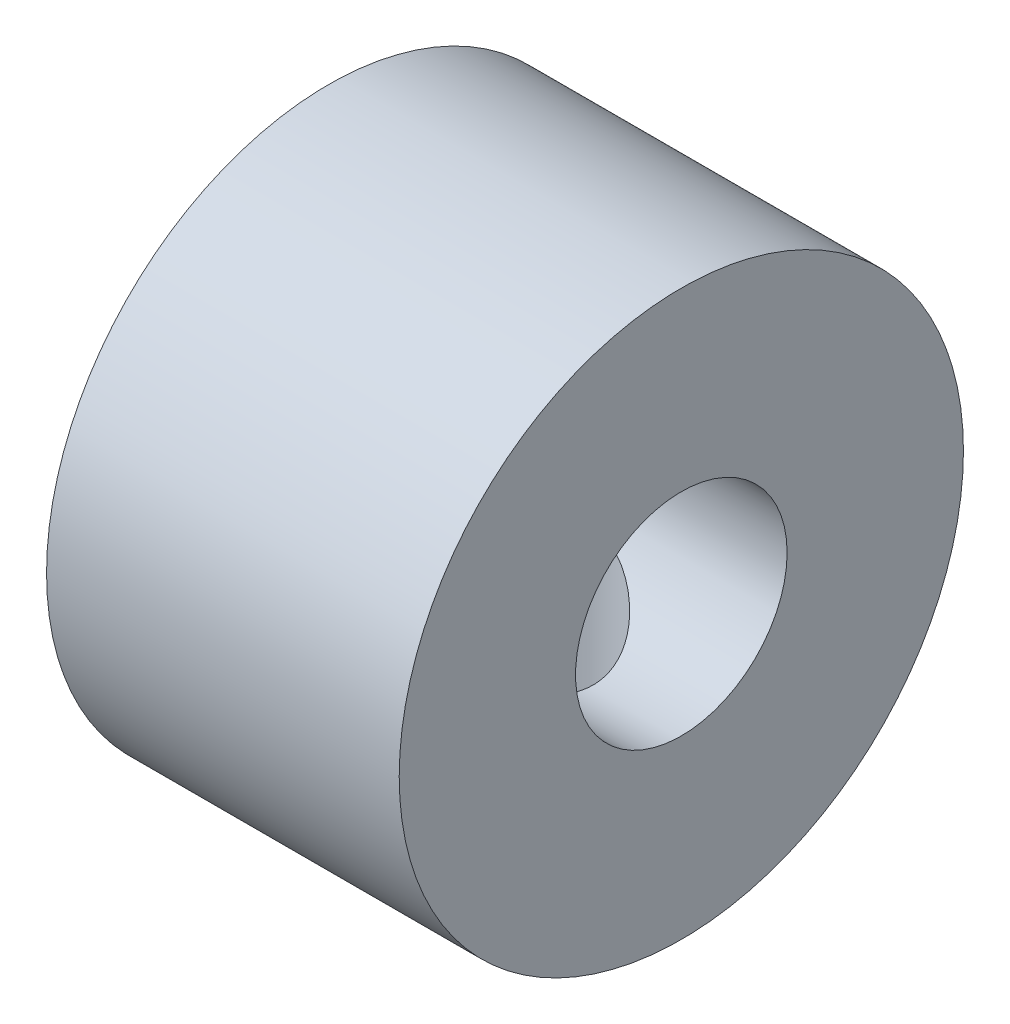
SolidWorks part; units mm, degrees
ref_plane "Front Plane" through (0, 0, 0) normal (0, 0, 1) x (1, 0, 0)
ref_plane "Top Plane" through (0, 0, 0) normal (0, 1, 0) x (1, 0, 0)
ref_plane "Right Plane" through (0, 0, 0) normal (1, 0, 0) x (0, 0, -1)
sketch "Sketch1" plane through (0, 0, 0) normal (1, 0, 0) x (0, 0, -1)
  circle A0 centre (0, 0) radius 1.5
  circle A1 centre (0, 0) radius 4
  dimension "D1" = 3
  dimension "D2" = 2.5
extrude "Boss-Extrude1" add sketch "Sketch1" along normal blind 5
sketch "Sketch2" plane through (0, 0, 0) normal (0, 1, 0) x (1, 0, 0)
  line L0 (5, -4) -> (5, 4) construction
  circle A0 centre (2.5, 0) radius 1.25
  dimension "D2" = 2.5
  dimension "D1" = 2.5
extrude "Cut-Extrude2" cut sketch "Sketch2" against normal through all contours A0
sketch "Sketch3" plane through (5, 0, 0) normal (1, 0, 0) x (0, 0, -1)
  line L0 (0, 0) -> (5.6987, 0)
